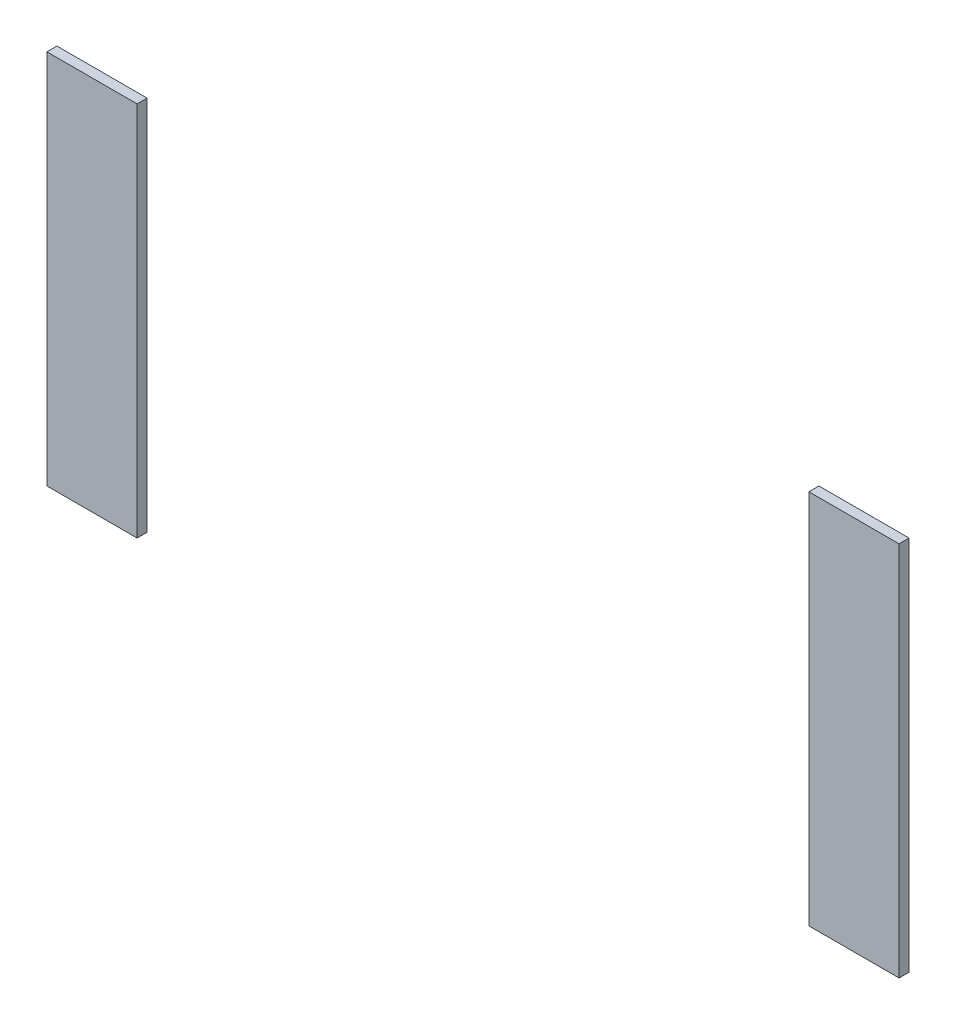
SolidWorks part; units mm, degrees
ref_plane "Front Plane" through (0, 0, 0) normal (0, 0, 1) x (1, 0, 0)
ref_plane "Top Plane" through (0, 0, 0) normal (0, 1, 0) x (1, 0, 0)
ref_plane "Right Plane" through (0, 0, 0) normal (1, 0, 0) x (0, 0, -1)
sketch "Sketch1" plane through (0, 0, 0) normal (0, 0, 1) x (1, 0, 0)
  line L0 (-425, 330) -> (425, 330)
  line L6 (-335, 142.5) -> (335, 142.5)
  line L9 (-425, -45) -> (-335, -45)
  line L10 (-425, -45) -> (-425, 330)
  line L11 (-425, 330) -> (-335, 330)
  line L12 (-335, -45) -> (-335, 330)
  line L13 (425, -45) -> (335, -45)
  line L14 (425, -45) -> (425, 330)
  line L15 (425, 330) -> (335, 330)
  line L16 (335, -45) -> (335, 330)
  point P0 (0, 0)
extrude "Boss-Extrude1" add sketch "Sketch1" along normal blind 10 contours L9 L12 L0 L10 | L16 L13 L14 L0
